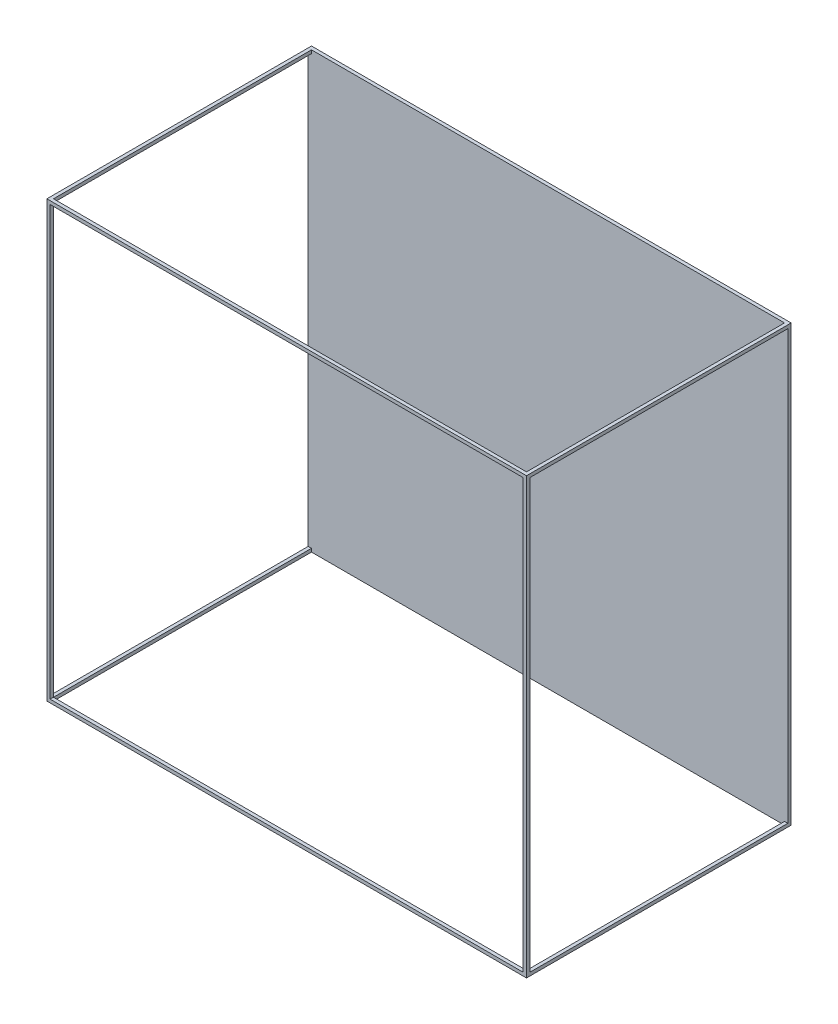
SolidWorks part; units mm, degrees
ref_plane "Alzado" through (0, 0, 0) normal (0, 0, 1) x (1, 0, 0)
ref_plane "Planta" through (0, 0, 0) normal (0, 1, 0) x (1, 0, 0)
ref_plane "Vista lateral" through (0, 0, 0) normal (1, 0, 0) x (0, 0, -1)
sketch "Croquis1" plane through (0, 0, 0) normal (0, 0, 1) x (1, 0, 0)
  line L0 (0, -55) -> (0, 55) construction
  line L1 (-72.5, 65.75) -> (72.5, 65.75)
  line L2 (-72.5, 65.75) -> (-72.5, -65.75)
  line L3 (-72.5, -65.75) -> (72.5, -65.75)
  line L4 (72.5, 65.75) -> (72.5, -65.75)
  line L5 (55, 0) -> (-55, 0) construction
  point P4 (-72.5, 0)
  point P5 (0, 65.75)
  dimension "D1" = 131.5
  dimension "D2" = 145
extrude "Saliente-Extruir1" add sketch "Croquis1" along normal mid plane 80
shell "Vaciado1" thickness 1
sketch "Croquis2" plane through (0, 65.75, 0) normal (0, 1, 0) x (1, 0, 0)
  line L0 (-72.5, -40) -> (-72.5, 40) construction
  line L1 (-71.5, 39) -> (71.5, 39)
  line L2 (-71.5, 39) -> (-71.5, -39)
  line L3 (-71.5, -39) -> (71.5, -39)
  line L4 (71.5, 39) -> (71.5, -39)
  line L5 (72.5, 40) -> (-72.5, 40) construction
  line L6 (72.5, -40) -> (72.5, 40) construction
  line L7 (72.5, -40) -> (-72.5, -40) construction
  dimension "D1" = 1
  dimension "D2" = 1
  dimension "D3" = 1
  dimension "D4" = 1
extrude "Cortar-Extruir1" cut sketch "Croquis2" against normal blind 160
sketch "Croquis3" plane through (72.5, 0, 0) normal (1, 0, 0) x (0, 0, -1)
  line L0 (-40, 65.75) -> (40, 65.75) construction
  line L1 (-39, 64.75) -> (39, 64.75)
  line L2 (-39, 64.75) -> (-39, -64.75)
  line L3 (-39, -64.75) -> (39, -64.75)
  line L4 (39, 64.75) -> (39, -64.75)
  line L5 (40, -65.75) -> (40, 65.75) construction
  line L6 (-40, -65.75) -> (40, -65.75) construction
  line L7 (-40, -65.75) -> (-40, 65.75) construction
  dimension "D1" = 1
  dimension "D2" = 1
  dimension "D3" = 1
  dimension "D4" = 1
extrude "Cortar-Extruir2" cut sketch "Croquis3" against normal blind 180
